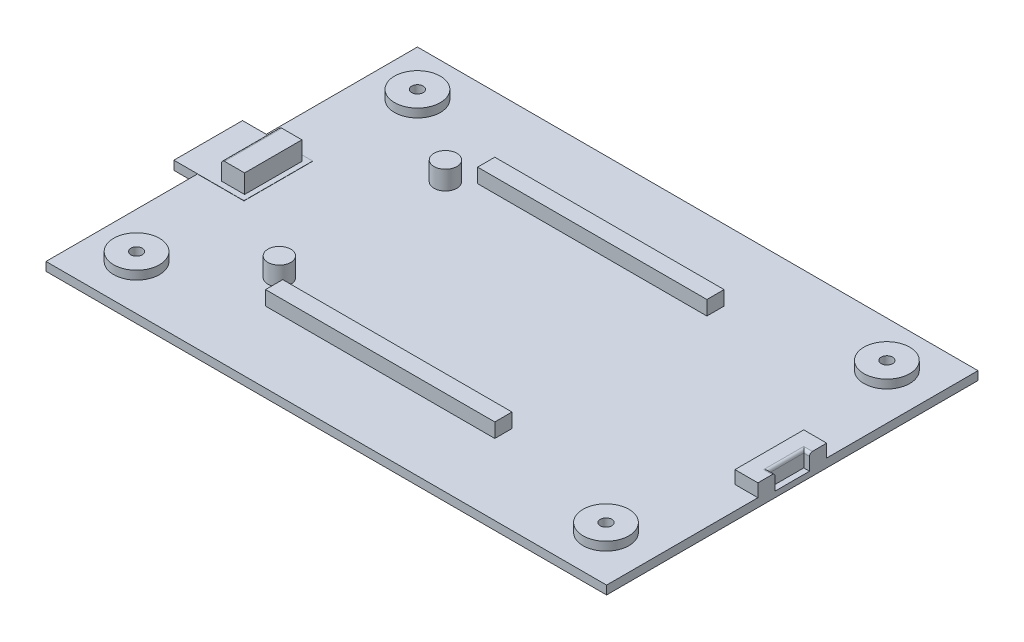
SolidWorks part; units mm, degrees
material "PLA"
ref_plane "前视基准面" through (0, 0, 0) normal (0, 0, 1) x (1, 0, 0)
ref_plane "上视基准面" through (0, 0, 0) normal (0, 1, 0) x (1, 0, 0)
ref_plane "右视基准面" through (0, 0, 0) normal (1, 0, 0) x (0, 0, -1)
other "Configuration Table"
sketch "草图1" plane through (0, 0, 0) normal (0, 1, 0) x (1, 0, 0)
  line L0 (-51.7144, -9.4544) -> (-55.8167, -9.4544)
  line L1 (-51.7144, 16.9583) -> (46.0856, 16.9583)
  line L2 (-51.7144, 16.9583) -> (-51.7144, -9.4544)
  line L3 (-51.7144, -47.8417) -> (46.0856, -47.8417)
  line L4 (46.0856, 16.9583) -> (46.0856, -47.8417)
  line L5 (-51.7144, 16.9583) -> (46.0856, -47.8417) construction
  line L6 (-51.7144, -47.8417) -> (46.0856, 16.9583) construction
  line L7 (-55.8167, -9.4544) -> (-55.8167, -21.429)
  line L8 (-51.8144, -9.3544) -> (-51.8144, 17.0583) construction
  line L9 (46.1856, -47.9417) -> (-51.8144, -47.9417) construction
  line L10 (-55.8167, -21.429) -> (-51.7144, -21.429)
  line L11 (-51.7144, -21.429) -> (-51.7144, -47.8417)
  line L12 (-51.8144, -9.3544) -> (-55.9167, -9.3544) construction
  line L13 (-55.9167, -21.529) -> (-51.8144, -21.529) construction
  line L14 (-55.9167, -9.3544) -> (-55.9167, -21.529) construction
  point P0 (0, 0)
  dimension "D1" = 97.8
  dimension "D2" = 64.8
  dimension "D3" = 0.1
  dimension "D4" = 0.1
  dimension "D5" = 0.1
  dimension "D6" = 0.1
  dimension "D7" = 0.1
extrude "凸台-拉伸1" add sketch "草图1" along normal blind 1.5
sketch "草图2" plane through (0, 0, 0) normal (0, -1, 0) x (1, 0, 0)
  line L0 (-51.7144, 47.8417) -> (46.0856, 47.8417) construction
  line L2 (-51.7144, 21.429) -> (-51.7144, 47.8417) construction
  circle A0 centre (-43.8144, -9.0583) radius 6
  circle A1 centre (-43.8144, 39.9417) radius 6
  circle A2 centre (38.0856, -9.0583) radius 6
  circle A3 centre (38.0856, 39.9417) radius 6
  circle A4 centre (-43.8144, -9.0583) radius 4 construction
  dimension "D1" = 12
  dimension "D2" = 12
  dimension "D3" = 12
  dimension "D4" = 12
  dimension "D5" = 7.9
  dimension "D6" = 7.9
extrude "切除-拉伸1" cut sketch "草图2" against normal blind 0.1
sketch "草图11" plane through (0, 0, 0) normal (0, -1, 0) x (1, 0, 0)
  line L0 (-55.8167, 9.4544) -> (-55.8167, 21.429) construction
  line L1 (-43.5867, 9.4544) -> (-55.8167, 9.4544)
  line L2 (-43.5867, 9.4544) -> (-43.5867, 21.429)
  line L3 (-43.5867, 21.429) -> (-55.8167, 21.429)
  line L4 (-55.8167, 9.4544) -> (-55.8167, 21.429)
  line L6 (-55.8167, 21.429) -> (-51.7144, 21.429) construction
  line L8 (-51.7144, 9.4544) -> (-55.8167, 9.4544) construction
  line L9 (-48.5867, 14.1953) -> (-48.5867, 16.6882) construction
  line L10 (-25.9144, 32.929) -> (-25.9144, -2.0456) construction
  line L11 (-48.389, 32.929) -> (-25.9144, 32.929) construction
  line L13 (-25.9144, 15.4417) -> (-37.5911, 15.4417) construction
  circle A0 centre (-28.9144, 29.929) radius 2
  circle A1 centre (-28.9144, 0.9544) radius 2
  dimension "D2" = 4
  dimension "D4" = 3
  dimension "D1" = 5
  dimension "D3" = 3
extrude "充电板档板凸台-拉伸5" add sketch "草图11" against normal up to surface (1.54 mm away)
sketch "草图13" plane through (0, 0, 0) normal (0, -1, 0) x (1, 0, 0)
  line L1 (-48.389, 32.929) -> (-25.9144, 32.929) construction
  line L2 (-25.9144, 32.929) -> (-25.9144, -2.0456) construction
  line L3 (-25.9144, 15.4417) -> (-36.6222, 15.4417) construction
  line L4 (-48.5667, 14.1953) -> (-48.5667, 16.6882) construction
  line L5 (-48.4667, 10.4417) -> (-44.4667, 10.4417)
  line L6 (-48.4667, 10.4417) -> (-48.4667, 20.4417)
  line L7 (-48.4667, 20.4417) -> (-44.4667, 20.4417)
  line L8 (-44.4667, 10.4417) -> (-44.4667, 20.4417)
  circle A1 centre (-28.9144, 29.929) radius 2
  circle A2 centre (-28.9144, 0.9544) radius 2
  dimension "D1" = 4
  dimension "D2" = 3
  dimension "D3" = 3
  dimension "D4" = 4
  dimension "D5" = 10
  dimension "D6" = 0.1
extrude "TypeC支撑凸台-拉伸2" add sketch "草图13" against normal up to surface (4.8 mm away)
sketch "草图14" plane through (0, 0, 0) normal (0, -1, 0) x (1, 0, 0)
  line L1 (45.0856, 12.4417) -> (45.0856, 18.4417)
  line L2 (45.0856, 18.4417) -> (46.0856, 18.4417)
  line L3 (46.0856, 18.4417) -> (46.0856, 21.4417)
  line L4 (46.0856, 47.8417) -> (46.0856, -16.9583) construction
  line L5 (46.0856, 21.4417) -> (42.0856, 21.4417)
  line L6 (42.0856, 21.4417) -> (42.0856, 9.4417)
  line L7 (42.0856, 9.4417) -> (46.0856, 9.4417)
  line L8 (46.0856, 9.4417) -> (46.0856, 12.4417)
  line L9 (46.0856, 12.4417) -> (45.0856, 12.4417)
  line L10 (46.0856, 15.4417) -> (41.9652, 15.4417) construction
  line L11 (46.1856, 18.3417) -> (45.1856, 18.3417) construction
  line L12 (45.1856, 18.3417) -> (45.1856, 12.9417) construction
  dimension "D1" = 0.1
  dimension "D2" = 0.1
  dimension "D3" = 3
  dimension "D4" = 3
  dimension "D5" = 3
extrude "LED限位凸台-拉伸3" add sketch "草图14" along normal up to surface (2.25 mm away) from surface
fillet "LED限位圆角1" radius 0.5 4 edges at (-48.4667, 4.8, 15.4417) (45.0856, 3.75, 15.4417) (45.5856, 3.75, 18.4417) (45.5856, 3.75, 12.4417)
sketch "草图15" plane through (0, 0, 0) normal (0, -1, 0) x (1, 0, 0)
  circle A0 centre (-43.8144, -9.0583) radius 2
  circle A1 centre (-43.8144, 39.9417) radius 2
  circle A2 centre (38.0856, 39.9417) radius 2
  circle A3 centre (38.0856, -9.0583) radius 2
  circle A4 centre (38.0856, 39.9417) radius 6 construction
  circle A5 centre (38.0856, -9.0583) radius 6 construction
  circle A6 centre (-43.8144, -9.0583) radius 6 construction
  circle A7 centre (-43.8144, 39.9417) radius 6 construction
  dimension "D1" = 4
  dimension "D2" = 4
  dimension "D3" = 4
  dimension "D4" = 4
extrude "螺丝孔位切除-拉伸2" cut sketch "草图15" against normal up to next
sketch "草图16" plane through (0, 0, 0) normal (0, -1, 0) x (1, 0, 0)
  circle A0 centre (38.0856, 39.9417) radius 1
  circle A1 centre (38.0856, -9.0583) radius 1
  circle A2 centre (-43.8144, -9.0583) radius 1
  circle A3 centre (-43.8144, -9.0583) radius 6 construction
  circle A8 centre (-43.8144, 39.9417) radius 6 construction
  circle A9 centre (38.0856, 39.9417) radius 6 construction
  circle A10 centre (38.0856, -9.0583) radius 6 construction
  circle A12 centre (38.0856, 39.9417) radius 4
  circle A13 centre (38.0856, -9.0583) radius 4
  circle A14 centre (-43.8144, -9.0583) radius 4
  circle A15 centre (-43.8144, 39.9417) radius 4
  circle A16 centre (-43.8144, 39.9417) radius 1
  dimension "D3" = 8
  dimension "D4" = 8
  dimension "D5" = 8
  dimension "D6" = 8
  dimension "D1" = 3
  dimension "D2" = 3
extrude "螺丝孔凸台-拉伸4" add sketch "草图16" along normal up to surface (1.5 mm away) from surface
sketch "草图17" plane through (0, 0, 0) normal (0, -1, 0) x (1, 0, 0)
  line L0 (45.0856, 12.4417) -> (46.1856, 12.4417) construction
  line L1 (45.0856, 18.4417) -> (45.0856, 12.4417) construction
  line L2 (46.1856, 18.4417) -> (45.0856, 18.4417) construction
  line L3 (45.0856, 12.4417) -> (46.0856, 12.4417)
  line L4 (45.0856, 18.4417) -> (45.0856, 12.4417)
  line L5 (46.0856, 18.4417) -> (45.0856, 18.4417)
  line L6 (46.0856, 12.4417) -> (46.0856, 18.4417)
  line L7 (46.0856, 47.8417) -> (46.0856, -16.9583) construction
extrude "切除-拉伸2" cut sketch "草图17" along normal blind 0.5 from surface at -1.5 starting at face at (-43.8144, 1.5, 43.9417)
sketch "草图18" plane through (0, 1.5, 0) normal (0, 1, 0) x (1, 0, 0)
  line L0 (-25.8144, 0.5583) -> (-25.8144, -1.4417) construction
  line L1 (14.1856, 4.5583) -> (-25.8144, 4.5583)
  line L2 (14.1856, 4.5583) -> (14.1856, 1.5583)
  line L3 (14.1856, 1.5583) -> (-25.8144, 1.5583)
  line L4 (-25.8144, 4.5583) -> (-25.8144, 1.5583)
  line L7 (14.1856, -32.4417) -> (-25.8144, -32.4417)
  line L8 (14.1856, -32.4417) -> (14.1856, -35.4417)
  line L9 (14.1856, -35.4417) -> (-25.8144, -35.4417)
  line L10 (-25.8144, -32.4417) -> (-25.8144, -35.4417)
  line L11 (14.1856, -31.4417) -> (14.1856, -29.4417) construction
  dimension "D1" = 3
  dimension "D2" = 3
extrude "凸台-拉伸2" add sketch "草图18" along normal up to surface (2.5 mm away)
